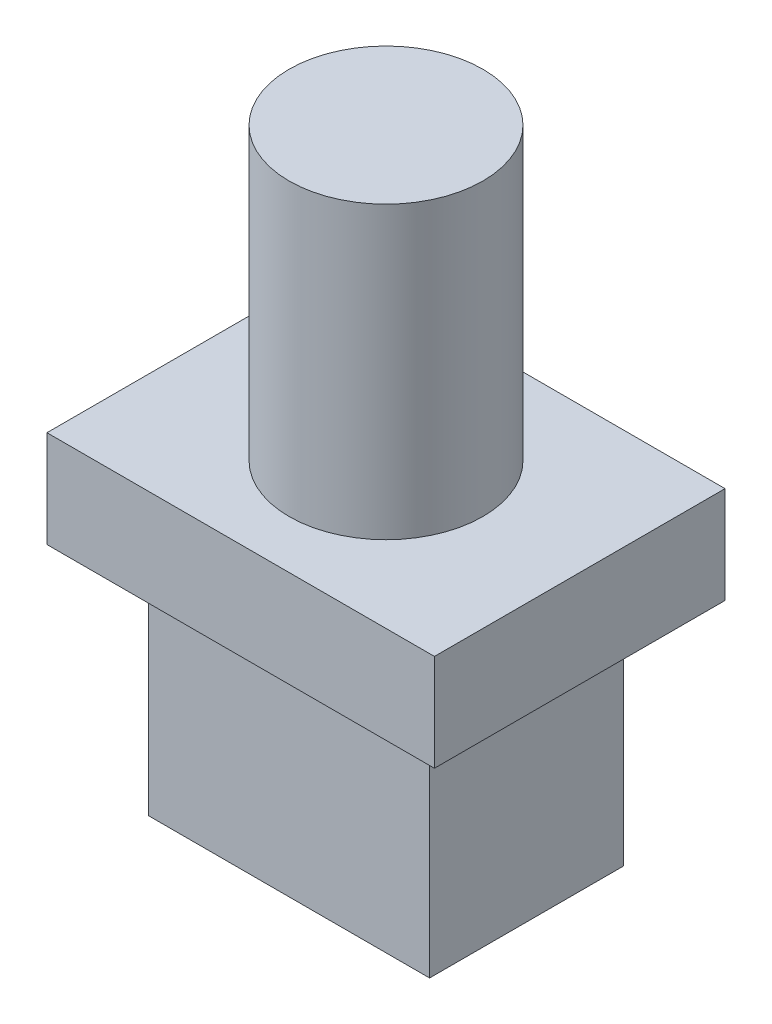
SolidWorks part; units mm, degrees
ref_plane "前视基准面" through (0, 0, 0) normal (0, 0, 1) x (1, 0, 0)
ref_plane "上视基准面" through (0, 0, 0) normal (0, 1, 0) x (1, 0, 0)
ref_plane "右视基准面" through (0, 0, 0) normal (1, 0, 0) x (0, 0, -1)
other "Configuration Table"
sketch "草图1" plane through (0, 0, 0) normal (0, 1, 0) x (1, 0, 0)
  line L0 (0, 0) -> (29, 0)
  line L1 (29, 0) -> (29, 20)
  line L2 (29, 20) -> (0, 20)
  line L3 (0, 20) -> (0, 0)
  dimension "D1" = 29
  dimension "D2" = 20
extrude "凸台-拉伸1" add sketch "草图1" along normal blind 24
sketch "草图2" plane through (0, 24, 0) normal (0, 1, 0) x (1, 0, 0)
  line L0 (0, 10) -> (29, 10)
  line L1 (0, 20) -> (0, 0) construction
  line L2 (29, 0) -> (29, 20) construction
  line L3 (14.5, 20) -> (14.5, 0)
  line L4 (29, 20) -> (0, 20) construction
  line L5 (0, 0) -> (29, 0) construction
  line L6 (14.5, 0) -> (34.5, 0)
  line L7 (29, 10) -> (34.5, 10)
  line L8 (34.5, 10) -> (34.5, 25)
  line L9 (34.5, 25) -> (-5.5, 25)
  line L10 (-5.5, 25) -> (-5.5, -5)
  line L11 (-5.5, -5) -> (34.5, -5)
  line L12 (34.5, -5) -> (34.5, 10)
  line M1 (0, 20) -> (0, 0)
  line M2 (0, 0) -> (29, 0)
  line M3 (29, 0) -> (29, 20)
  line M4 (29, 20) -> (0, 20)
extrude "凸台-拉伸2" add sketch "草图2" along normal blind 10 contours L3 L0 M1 M2 | L11 L12 L6 L7 L8 L9 L10 M2 M1 M4 M3 | L0 L3 M2 M3 | L6 L12 L7 M3 | L3 L0 M4 M3 | L3 L0 M4 M1
sketch "草图3" plane through (0, 34, 0) normal (0, 1, 0) x (1, 0, 0)
  line L0 (-5.5, 10) -> (34.5, 10)
  line L1 (-5.5, 25) -> (-5.5, -5) construction
  line L2 (34.5, -5) -> (34.5, 25) construction
  line L3 (14.5, 25) -> (14.5, -5)
  line L4 (34.5, 25) -> (-5.5, 25) construction
  line L5 (-5.5, -5) -> (34.5, -5) construction
  circle A0 centre (14.5, 10) radius 10
  dimension "D1" = 20
extrude "凸台-拉伸3" add sketch "草图3" along normal blind 30 contours L3 A0 L0 | L0 A0 L3 | L3 A0 L0 | L0 A0 L3
